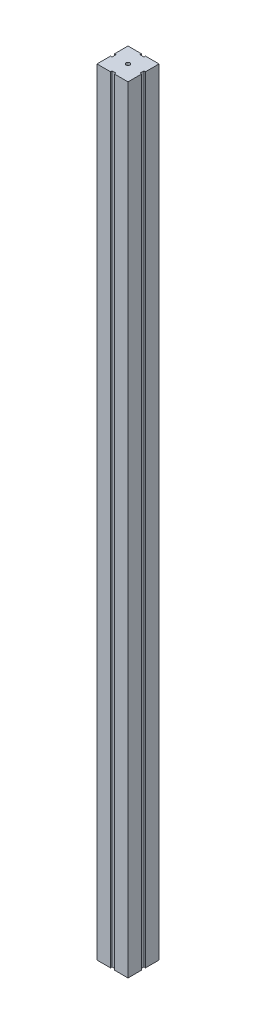
SolidWorks part; units mm, degrees
ref_plane "Front Plane" through (0, 0, 0) normal (0, 0, 1) x (1, 0, 0)
ref_plane "Top Plane" through (0, 0, 0) normal (0, 1, 0) x (1, 0, 0)
ref_plane "Right Plane" through (0, 0, 0) normal (1, 0, 0) x (0, 0, -1)
sketch "Sketch1" plane through (0, 0, 0) normal (0, 1, 0) x (1, 0, 0)
  line L0 (25.4, -3.175) -> (22.8624, -3.175)
  line L2 (-25.4, 25.4) -> (-25.4, 3.175)
  line L3 (-25.4, -25.4) -> (-3.175, -25.4)
  line L4 (25.4, 25.4) -> (25.4, 3.175)
  line L5 (-3.175, 25.4) -> (-3.175, 22.8624)
  line L6 (-3.175, 22.8624) -> (3.175, 22.8624)
  line L7 (3.175, 25.4) -> (3.175, 22.8624)
  line L8 (22.8624, 3.175) -> (22.8624, -3.175)
  line L9 (25.4, 3.175) -> (22.8624, 3.175)
  line L10 (-3.175, -25.4) -> (-3.175, -22.8624)
  line L11 (3.175, -22.8624) -> (-3.175, -22.8624)
  line L12 (3.175, -25.4) -> (3.175, -22.8624)
  line L13 (-25.4, 3.175) -> (-22.8624, 3.175)
  line L14 (-22.8624, -3.175) -> (-22.8624, 3.175)
  line L15 (-25.4, -3.175) -> (-22.8624, -3.175)
  line L16 (3.175, 25.4) -> (25.4, 25.4)
  line L17 (25.4, -3.175) -> (25.4, -25.4)
  line L18 (3.175, -25.4) -> (25.4, -25.4)
  line L19 (-25.4, -3.175) -> (-25.4, -25.4)
  line L20 (-25.4, 25.4) -> (-3.175, 25.4)
  circle A0 centre (0, 0) radius 3.175
  point P0 (0, 0)
  point P13 (0, 22.8624)
  point P26 (0, 0)
  dimension "D4" = 4
extrude "Boss-Extrude2" add sketch "Sketch1" along normal blind 1270
